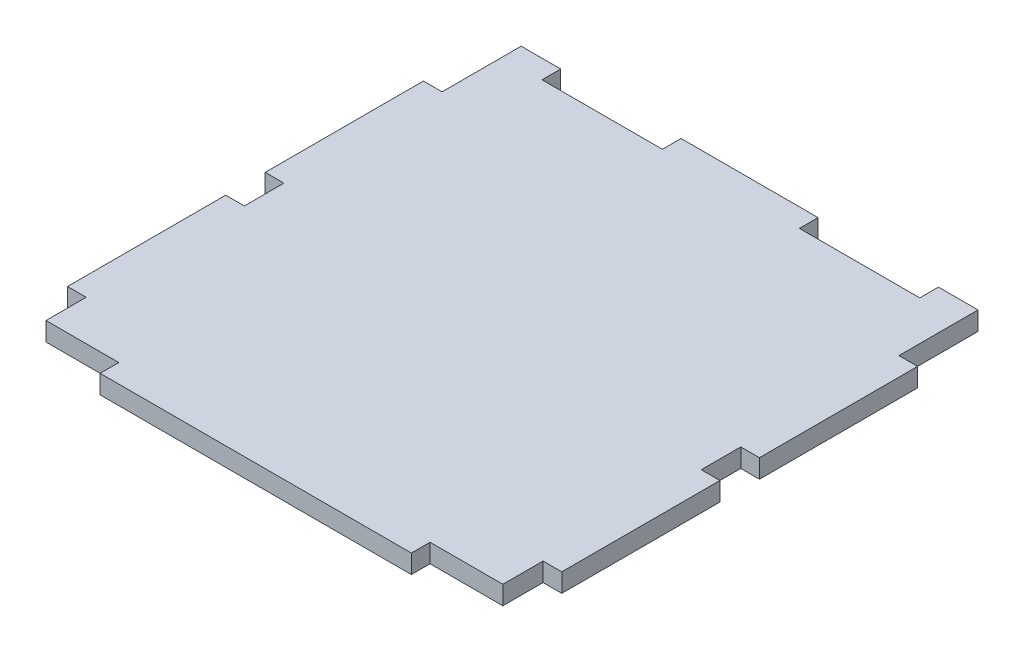
SolidWorks part; units mm, degrees
ref_plane "Front Plane" through (0, 0, 0) normal (0, 0, 1) x (1, 0, 0)
ref_plane "Top Plane" through (0, 0, 0) normal (0, 1, 0) x (1, 0, 0)
ref_plane "Right Plane" through (0, 0, 0) normal (1, 0, 0) x (0, 0, -1)
sketch "Sketch1" plane through (0, 0, 0) normal (0, 1, 0) x (1, 0, 0)
  line L0 (0, 38.155) -> (0, -38.155) construction
  line L1 (36.685, -38.155) -> (-36.685, -38.155)
  line L2 (36.685, -38.155) -> (36.685, -28.695)
  line L3 (-36.685, 38.155) -> (-36.685, 41.155)
  line L4 (-36.685, -38.155) -> (-36.685, -28.695)
  line L5 (36.685, -38.155) -> (-36.685, 38.155) construction
  line L6 (36.685, 38.155) -> (-36.685, -38.155) construction
  line L7 (-39.685, -3.295) -> (-36.685, -3.295)
  line L8 (-36.685, 3.055) -> (-39.685, 3.055)
  line L9 (-39.685, 3.055) -> (-39.685, 28.455)
  line L10 (-39.685, 28.455) -> (-36.685, 28.455)
  line L11 (-36.685, -28.695) -> (-39.685, -28.695)
  line L12 (-39.685, -28.695) -> (-39.685, -3.295)
  line L13 (39.685, 28.455) -> (36.685, 28.455)
  line L14 (36.685, -28.695) -> (39.685, -28.695)
  line L15 (39.685, -28.695) -> (39.685, -3.295)
  line L16 (39.685, -3.295) -> (36.685, -3.295)
  line L17 (36.685, 3.055) -> (39.685, 3.055)
  line L18 (39.685, 3.055) -> (39.685, 28.455)
  line L19 (-36.685, 28.455) -> (-36.685, 38.155)
  line L20 (-36.685, -3.295) -> (-36.685, 3.055)
  line L21 (36.685, 28.455) -> (36.685, 38.155)
  line L22 (36.685, -3.295) -> (36.685, 3.055)
  line L23 (-30.335, 38.155) -> (-30.335, 41.155)
  line L24 (-30.335, 41.155) -> (-36.515, 41.155)
  line L25 (-36.685, 41.155) -> (-36.515, 41.155)
  line L26 (30.335, 38.155) -> (30.335, 41.155)
  line L27 (30.335, 41.155) -> (36.515, 41.155)
  line L28 (-11, 41.155) -> (11, 41.155)
  line L29 (30.335, 38.155) -> (11, 38.155)
  line L30 (-11, 38.155) -> (-30.335, 38.155)
  line L31 (36.515, 41.155) -> (36.685, 41.155)
  line L32 (36.685, 41.155) -> (36.685, 38.155)
  line L33 (11, 41.155) -> (11, 38.155)
  line L34 (-36.685, -35.155) -> (-24.995, -35.155)
  line L35 (-11, 41.155) -> (-11, 38.155)
  line L36 (-24.995, -35.155) -> (-24.995, -38.155)
  line L37 (24.995, -35.155) -> (24.995, -38.155)
  line L38 (36.685, -35.155) -> (24.995, -35.155)
  point P0 (0, 0)
  dimension "D1" = 73.37
  dimension "D2" = 6.35
  dimension "D3" = 3
  dimension "D4" = 6.35
  dimension "D5" = 6.35
  dimension "D6" = 25.4
  dimension "D7" = 3
  dimension "D8" = 25.4
  dimension "D9" = 3
  dimension "D10" = 3
  dimension "D11" = 11
  dimension "D12" = 11
  dimension "D13" = 3
  dimension "D14" = 11.69
  dimension "D15" = 3
extrude "Boss-Extrude1" add sketch "Sketch1" along normal blind 3 contours L38 L2 L14 L15 L16 L22 L17 L18 L13 L21 L32 L31 L27 L26 L29 L33 L28 L35 L30 L23 L24 L25 L3 L19 L10 L9 L8 L20 L7 L12 L11 L4 L34 L36 L1 L37
